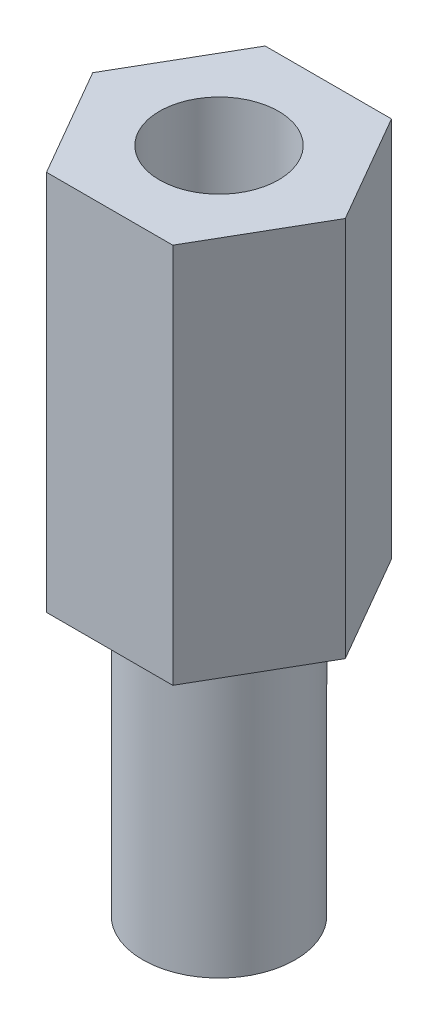
SolidWorks part; units mm, degrees
ref_plane "前视基准面" through (0, 0, 0) normal (0, 0, 1) x (1, 0, 0)
ref_plane "上视基准面" through (0, 0, 0) normal (0, 1, 0) x (1, 0, 0)
ref_plane "右视基准面" through (0, 0, 0) normal (1, 0, 0) x (0, 0, -1)
sketch "草图4" plane through (0, 0, 0) normal (0, 1, 0) x (1, 0, 0)
  line L0 (-12.7945, 0) -> (16.3015, 0) construction
  line L2 (1.325, -2.295) -> (2.65, 0)
  line L3 (2.65, 0) -> (1.325, 2.295)
  line L4 (1.325, 2.295) -> (-1.325, 2.295)
  line L5 (-1.325, 2.295) -> (-2.65, 0)
  line L6 (-2.65, 0) -> (-1.325, -2.295)
  line L7 (-1.325, -2.295) -> (1.325, -2.295)
  circle A0 centre (0, 0) radius 2.295 construction
  dimension "D1" = 5.3
extrude "凸台-拉伸1" add sketch "草图4" along normal blind 8
sketch "草图6" plane through (0, 0, 0) normal (0, -1, 0) x (-1, 0, 0)
  circle A0 centre (0, 0) radius 1.6
  dimension "D1" = 3.2
extrude "凸台-拉伸2" add sketch "草图6" along normal blind 6
cosmetic thread "装饰螺纹线1"
sketch "草图7" plane through (0, 8, 0) normal (0, 1, 0) x (1, 0, 0)
  circle A0 centre (0, 0) radius 1.25
  dimension "D1" = 2.5
extrude "切除-拉伸1" cut sketch "草图7" against normal blind 6
cosmetic thread "装饰螺纹线2"
